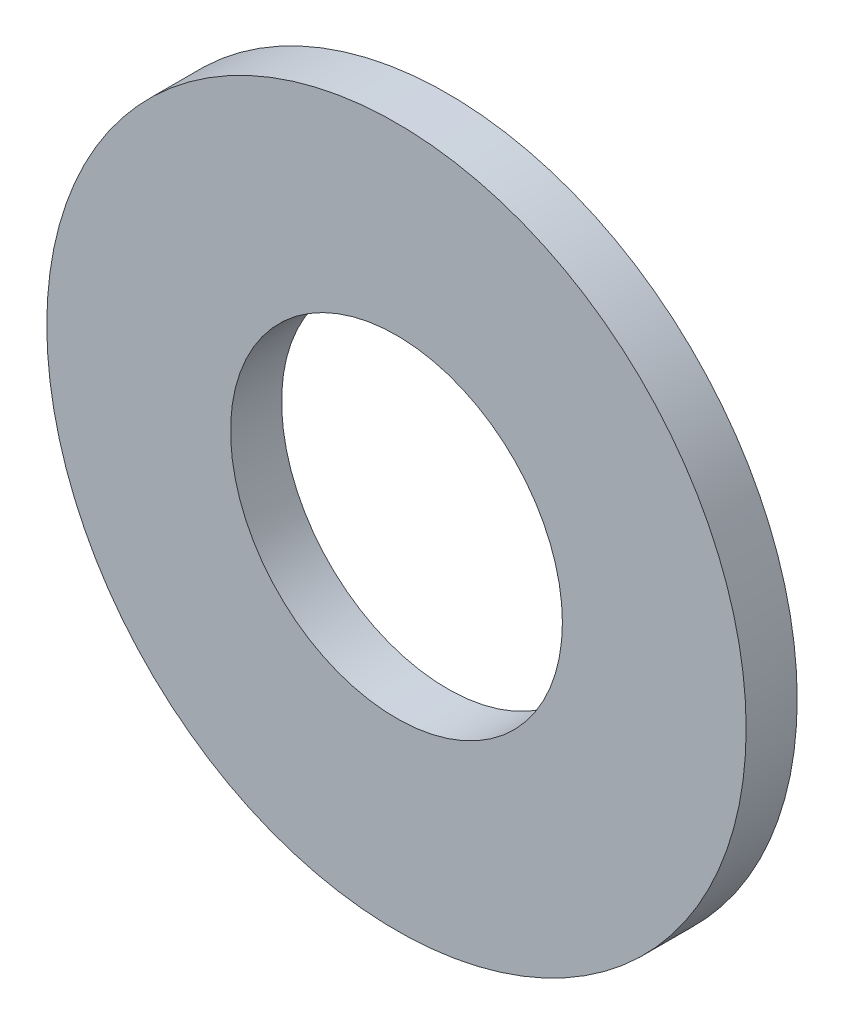
SolidWorks part; units mm, degrees
ref_plane "Piano frontale" through (0, 0, 0) normal (0, 0, 1) x (1, 0, 0)
ref_plane "Piano superiore" through (0, 0, 0) normal (0, 1, 0) x (1, 0, 0)
ref_plane "Piano destro" through (0, 0, 0) normal (1, 0, 0) x (0, 0, -1)
sketch "Schizzo2" plane through (0, 0, 0) normal (0, 0, 1) x (1, 0, 0)
  circle A0 centre (0, 0) radius 3.425
  circle A1 centre (0, 0) radius 1.625
  dimension "D1" = 3.25
  dimension "D2" = 6.85
extrude "Estrusione-Estrusione1" add sketch "Schizzo2" along normal blind 0.5
